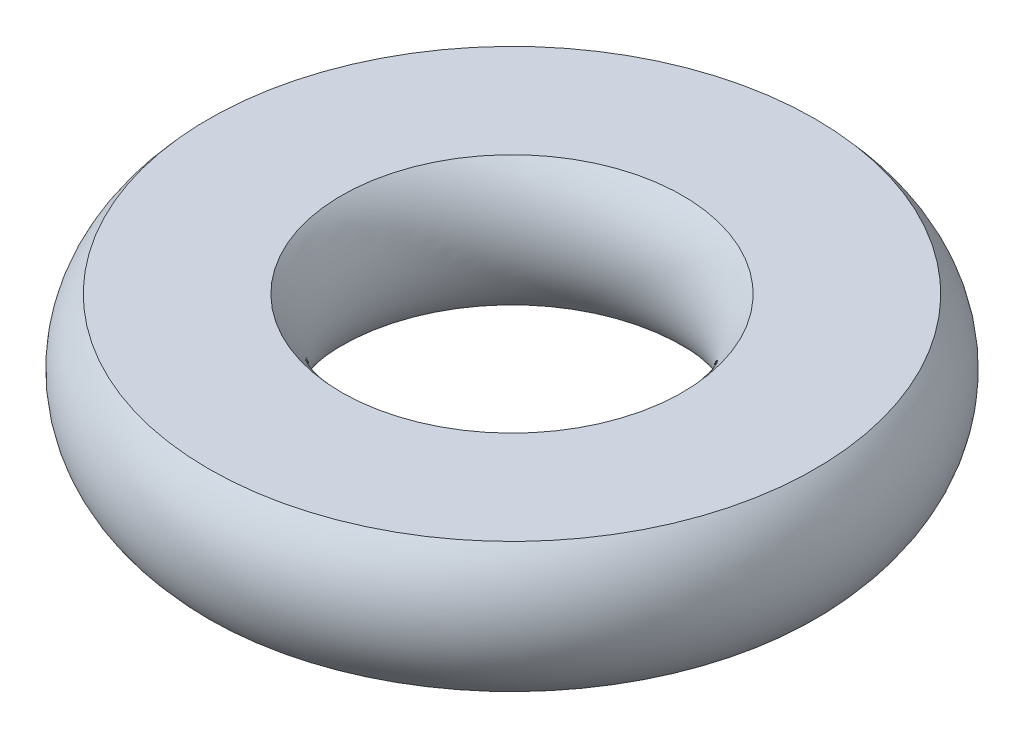
SolidWorks part; units mm, degrees
ref_plane "Front Plane" through (0, 0, 0) normal (0, 0, 1) x (1, 0, 0)
ref_plane "Top Plane" through (0, 0, 0) normal (0, 1, 0) x (1, 0, 0)
ref_plane "Right Plane" through (0, 0, 0) normal (1, 0, 0) x (0, 0, -1)
sketch "Sketch2" plane through (0, 0, 0) normal (0, 0, 1) x (1, 0, 0)
  line L0 (0, 0) -> (1.275, 0) construction
  line L1 (55, 0) -> (-55, 0) construction
  line L2 (0, 0.0675) -> (0, -0.0825)
  line L3 (0, -55) -> (0, 55) construction
  line L4 (0.9179, 0.35) -> (1.6321, 0.35)
  line L5 (0.9179, -0.35) -> (1.6321, -0.35)
  line L6 (0, -0.0675) -> (0, 0.0825)
  circle A0 centre (1.275, 0) radius 0.5
  arc A1 (1.6321, 0.35) -> (0.9179, 0.35) centre (1.275, 0) ccw
  arc A2 (1.6321, -0.35) -> (0.9179, -0.35) centre (1.275, 0) cw
  dimension "D2" = 1
  dimension "D1" = 1.275
  dimension "D3" = 0.15
  dimension "D4" = 0.35
revolve "Revolve1" add sketch "Sketch2" angle 360 about L2
